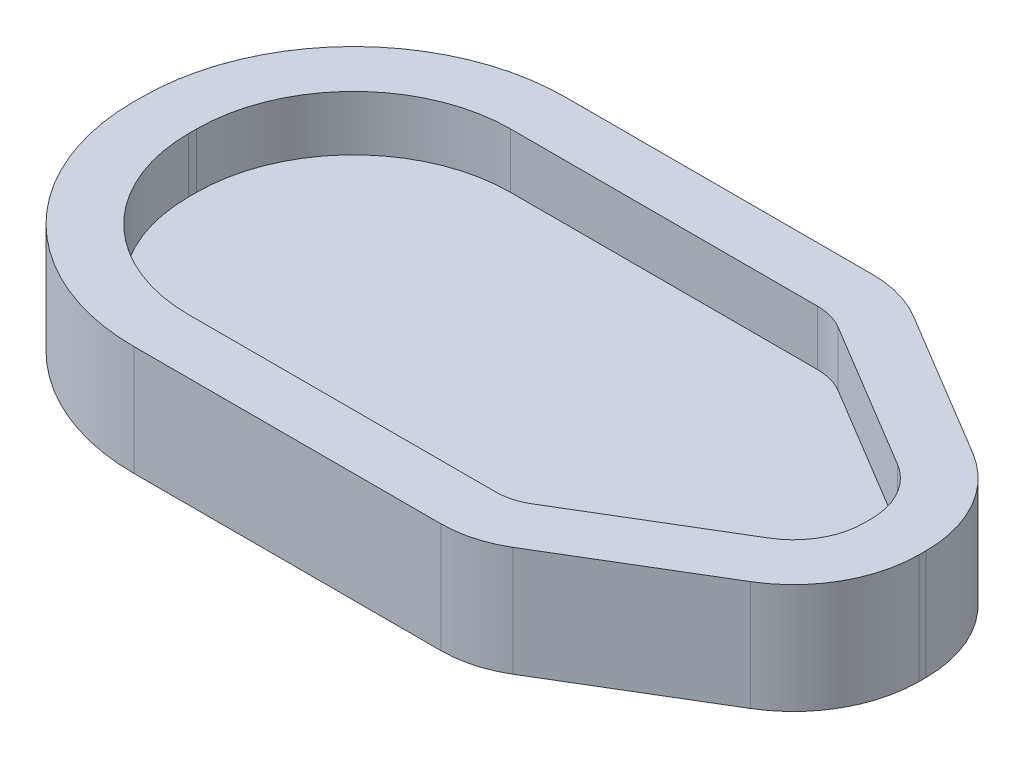
SolidWorks part; units mm, degrees
material "7075-O (SS)"
ref_plane "Piano frontale" through (0, 0, 0) normal (0, 0, 1) x (1, 0, 0)
ref_plane "Piano superiore" through (0, 0, 0) normal (0, 1, 0) x (1, 0, 0)
ref_plane "Piano destro" through (0, 0, 0) normal (1, 0, 0) x (0, 0, -1)
sketch "Sketch1" plane through (0, 0, 0) normal (0, 1, 0) x (1, 0, 0)
  line L1 (-25, -13.75) -> (25, -13.75)
  line L2 (-25, -13.75) -> (-25, 13.75)
  line L3 (-25, 13.75) -> (25, 13.75)
  line L4 (25, -13.75) -> (25, 13.75)
  line L5 (-25, -13.75) -> (25, 13.75) construction
  line L6 (-25, 13.75) -> (25, -13.75) construction
  point P0 (0, 0)
  dimension "D1" = 27.5
  dimension "D2" = 50
extrude "Boss-Extrude1" add sketch "Sketch1" along normal blind 7
fillet "Fillet1" radius 13.5 2 edges at (-25, 3.5, 13.75) (-25, 3.5, -13.75)
sketch "Sketch3" plane through (0, 7, 0) normal (0, 1, 0) x (1, 0, 0)
  line L0 (10, 13.75) -> (25, 4.75)
  line L1 (25, 13.75) -> (-11.5, 13.75) construction
  line L2 (25, -13.75) -> (25, 13.75) construction
  line L3 (25, 4.75) -> (25, 13.75)
  line L4 (25, 13.75) -> (10, 13.75)
  line L5 (0, 0) -> (25, 0) construction
  line L6 (25, -13.75) -> (10, -13.75)
  line L7 (25, -4.75) -> (25, -13.75)
  line L8 (10, -13.75) -> (25, -4.75)
  dimension "D1" = 15
  dimension "D2" = 9
extrude "Cut-Extrude1" cut sketch "Sketch3" against normal up to next
fillet "Fillet2" radius 8 2 edges at (25, 3.5, 4.75) (25, 3.5, -4.75)
fillet "Fillet3" radius 7 2 edges at (10, 3.5, 13.75) (10, 3.5, -13.75)
shell "Shell1" thickness 3.5
